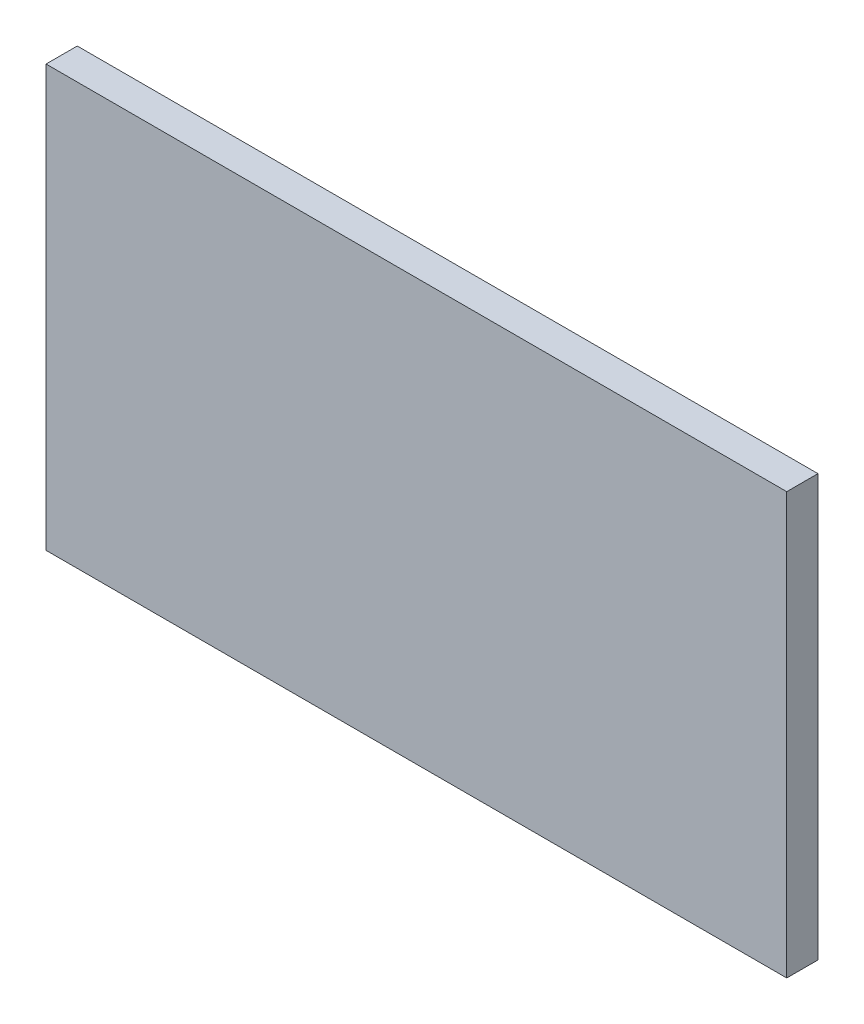
SolidWorks part; units mm, degrees
ref_plane "前视基准面" through (0, 0, 0) normal (0, 0, 1) x (1, 0, 0)
ref_plane "上视基准面" through (0, 0, 0) normal (0, 1, 0) x (1, 0, 0)
ref_plane "右视基准面" through (0, 0, 0) normal (1, 0, 0) x (0, 0, -1)
sketch "草图1" plane through (0, 0, 0) normal (0, 0, 1) x (1, 0, 0)
  line L1 (-11.87, 6.75) -> (11.87, 6.75)
  line L2 (-11.87, 6.75) -> (-11.87, -6.75)
  line L3 (-11.87, -6.75) -> (11.87, -6.75)
  line L4 (11.87, 6.75) -> (11.87, -6.75)
  line L5 (-11.87, 6.75) -> (11.87, -6.75) construction
  line L6 (-11.87, -6.75) -> (11.87, 6.75) construction
  point P1 (0, 0)
  dimension "D1" = 23.74
  dimension "D2" = 13.5
extrude "凸台-拉伸1" add sketch "草图1" along normal blind 1
